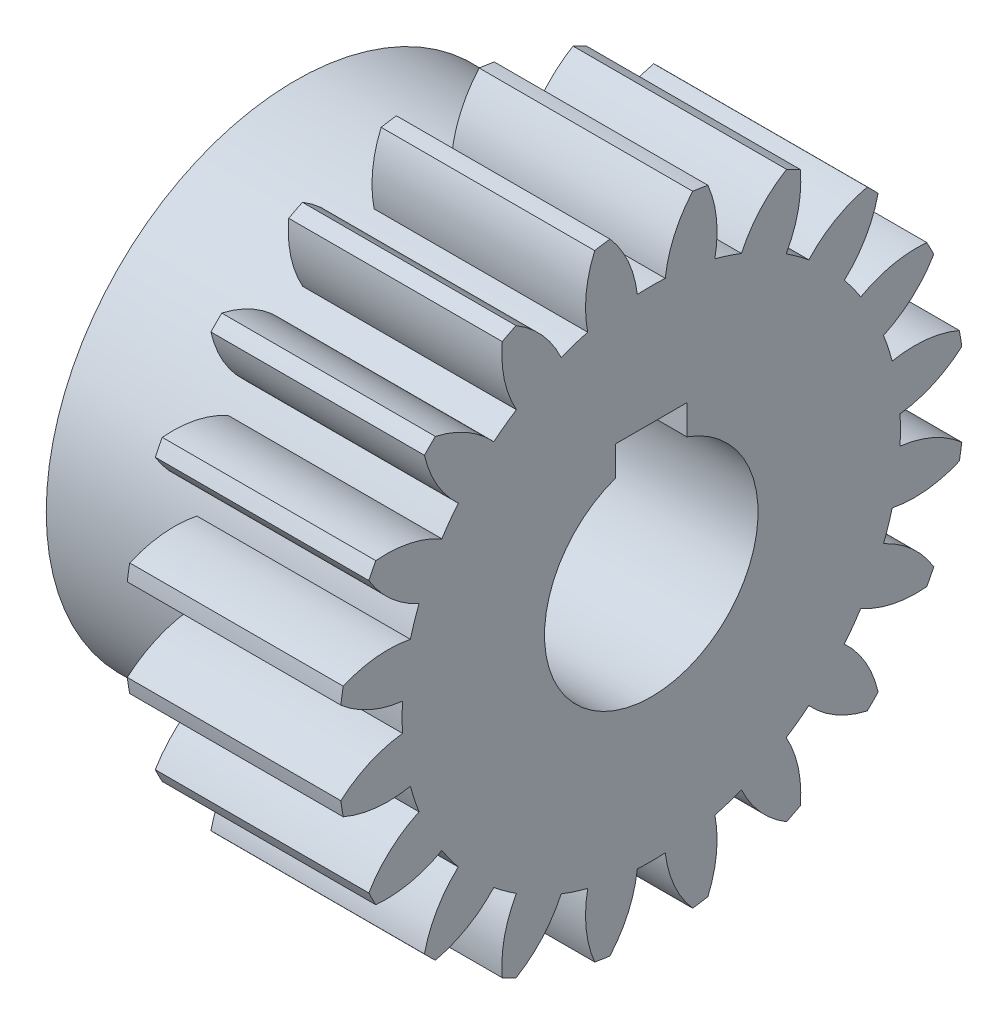
SolidWorks part; units mm, degrees
ref_plane "Plane1" through (0, 0, 0) normal (0, 0, 1) x (1, 0, 0)
ref_plane "Plane2" through (0, 0, 0) normal (0, 1, 0) x (1, 0, 0)
ref_plane "Plane3" through (0, 0, 0) normal (1, 0, 0) x (0, 0, -1)
other "Configuration Table"
sketch "HoldingSke" plane through (0, 0, 0) normal (0, 1, 0) x (1, 0, 0)
  line L0 (0, 0) -> (0.2349, -0.0855)
  line L1 (-15, 0) -> (100, 0) construction
  line L2 (0, 0) -> (-2.1039, 2.3779)
  line L3 (0, 0) -> (-11.863, 4.5341)
  line L4 (0, 0) -> (8.1152, 2.9537)
  line L5 (0, 0) -> (-46.8476, -17.4728)
  line L6 (0, 0) -> (-24.8689, -16.7791)
  line L7 (-2.1039, 2.3779) -> (8.6586, 51.2059)
  line L8 (-76.2, 54.61) -> (-72.9, 54.61)
  line L9 (-71.009, 38.7566) -> (-53.1078, 45.2721)
  line L10 (-76.2, 71.12) -> (104.1128, 71.12)
  line L11 (0, 0) -> (-30, 0)
  line L12 (-76.2, 101.6) -> (-76.073, 101.6)
  line L13 (24.9733, 27.94) -> (52.9518, 28.4284)
  line L14 (24.9733, 27.94) -> (24.9743, 27.94)
  line L15 (24.9733, 27.94) -> (100.4006, 29.5858)
  line L16 (-63.627, -4) -> (-12.827, -4)
  circle A0 centre (0, 0) radius 15
  circle A1 centre (0, 0) radius 34.999
  circle A2 centre (0, 0) radius 37.5
  circle A3 centre (0, 0) radius 15
  dimension "Hub_dia" = 75
  dimension "Bore" = 30
  dimension "MBD" = 30
  dimension "Pitch" = 0.25
  dimension "Overall_len" = 50
  dimension "Thickness" = 30
  dimension "OAL" = 50.0001
  dimension "T_dim" = 3.3
  dimension "Ap" = 20
  dimension "H" = 19.05
  dimension "Pitch_radius" = 180.3128
  dimension "Width" = 30
  dimension "Backlash" = 0.127
  dimension "Addendum_fac" = 1
  dimension "Dedendum_fac" = 1.25
  dimension "Clearance_fac" = 0.25
  dimension "Dedendum_add" = 0.001
  dimension "Module" = 4
sketch "BasProSke" plane through (0, 0, 0) normal (0, 1, 0) x (1, 0, 0)
  line L0 (-10, 0) -> (60, 0) construction
  line L1 (0, 0) -> (0, 44)
  line L2 (0, 0) -> (30, 0)
  line L3 (30, 0) -> (30, 44)
  line L4 (30, 44) -> (0, 44)
  dimension "Thickness" = 30
revolve "Base-Revolve" add sketch "BasProSke" angle 360 about L0
sketch "TooCutSke" plane through (0, 0, 0) normal (1, 0, 0) x (0, 0, -1)
  line L1 (0, 0) -> (0, 107) construction
  line L2 (0, 0) -> (-3.3605, 39.8586) construction
  line L3 (0, 0) -> (-12.4815, 78.8048) construction
  line L4 (-3.3605, 39.8586) -> (-6.2407, 39.4024) construction
  arc A0 (1.9617, 34.944) -> (-1.9617, 34.944) centre (0, 0) ccw
  arc A1 (5.8321, 43.6374) -> (-5.8321, 43.6374) centre (0, 0) ccw
  circle A2 centre (0, 0) radius 40 construction
  circle A3 centre (0, 0) radius 37.5877 construction
  arc A4 (-1.9617, 34.944) -> (-5.8321, 43.6374) centre (-17.8525, 33.0775) ccw
  arc A5 (5.8321, 43.6374) -> (1.9617, 34.944) centre (17.8525, 33.0775) ccw
extrude "ToothCut" cut sketch "TooCutSke" along normal through all
fillet "Breaks" [suppressed] radius 0.08
fillet "RootFillets" [suppressed] radius 1.001
pattern_circular "TeethCuts" count 20 every 18 about axis through (-10, 0, 0) along (1, 0, 0) of "ToothCut", "RootFillets", "Breaks"
sketch "HubNeaOneSke" plane through (0, 0, 0) normal (-1, 0, 0) x (0, 0, 1)
  circle A0 centre (0, 0) radius 34.999
extrude "HubNearOne" add sketch "HubNeaOneSke" along normal blind 20.0001
sketch "HubNeaBotSke" plane through (0, 0, 0) normal (-1, 0, 0) x (0, 0, 1)
  circle A0 centre (0, 0) radius 34.999
extrude "HubNearBoth" [suppressed] add sketch "HubNeaBotSke" along normal blind 10
ref_plane "FarPln" through (30, 0, 0) normal (1, 0, 0) x (0, 0, -1)
sketch "HubFarSke" plane through (30, 0, 0) normal (1, 0, 0) x (0, 0, -1)
  circle A0 centre (0, 0) radius 34.999
extrude "HubFar" [suppressed] add sketch "HubFarSke" along normal blind 10
sketch "BorSke" plane through (0, 0, 0) normal (1, 0, 0) x (0, 0, -1)
  circle A0 centre (0, 0) radius 15
  dimension "Diameter" = 30
extrude "Bore" cut sketch "BorSke" along normal mid plane 100.0001
sketch "KeySke" plane through (0, 0, 0) normal (1, 0, 0) x (0, 0, -1)
  line L0 (-5, 0) -> (-5, 18.3)
  line L1 (-5, 18.3) -> (5, 18.3)
  line L2 (5, 18.3) -> (5, 0)
  line L3 (0, 0) -> (0, 34) construction
  line L4 (-5, 0) -> (5, 0)
  dimension "Offset" = 18.3
  dimension "Width" = 10
extrude "Keyway" cut sketch "KeySke" along normal mid plane 100.0001
pattern_circular "Keyway2" [suppressed] count 2 every 90 about axis through (-10, 0, 0) along (1, 0, 0)
equation "' \"Module@HoldingSke\" = 6.35"
equation "' \"Num_teeth@HoldingSke\" = 12"
equation "' \"Ap@HoldingSke\" =  20"
equation "' \"Ap@HoldingSke\" = 20"
equation "' \"Width@HoldingSke\" = 0.5 * 25.4"
equation "' \"Hub_dia@HoldingSke\"= 1 * 25.4"
equation "' \"Hub_dia@HoldingSke\" = 1 * 25.4"
equation "' \"Overall_len@HoldingSke\" = 1.0 * 25.4"
equation "' \"Bore@HoldingSke\" = 0.75 * 25.4"
equation "' \"T_dim@HoldingSke\" = 0.1 * 25.4"
equation "' \"Width@KeySke\" = 0.25 * 25.4"
equation "' \"Show_teeth@HoldingSke\" = 13"
equation "' \"Backlash@HoldingSke\" = 0.009 * 25.4"
equation "' \"Addendum_fac@HoldingSke\" = 1.0"
equation "' \"Dedendum_fac@HoldingSke\" = 1.25"
equation "' \"Dedendum_add@HoldingSke\" = 0.00005 * 25.4"
equation "' \"Clearance_fac@HoldingSke\" = 0.25"
equation "\"Pitch@HoldingSke\" = 1 / \"Module@HoldingSke\""
equation "\"Overcut_dia@TooCutSke\" = (\"Num_teeth@HoldingSke\" + 2 * \"Addendum_fac@HoldingSke\") / \"Pitch@HoldingSke\" + 0.002 * 25.4"
equation "\"Pitch_dia@TooCutSke\" = \"Num_teeth@HoldingSke\" / \"Pitch@HoldingSke\""
equation "\"Base_dia@TooCutSke\" = \"Num_teeth@HoldingSke\" / \"Pitch@HoldingSke\" * cos((\"Ap@HoldingSke\"  * 3.14159265 / 180))"
equation "\"Root_dia@TooCutSke\" = (\"Num_teeth@HoldingSke\" + 2) / \"Pitch@HoldingSke\" - 2 * (\"Addendum_fac@HoldingSke\" + \"Dedendum_fac@HoldingSke\") / \"Pitch@HoldingSke\" - \"Dedendum_add@HoldingSke\" * 2"
equation "\"Half_ang@TooCutSke\" = 180 / \"Num_teeth@HoldingSke\""
equation "\"Half_CT@TooCutSke\" = \"Num_teeth@HoldingSke\" / \"Pitch@HoldingSke\" * sin((3.14159265 / 2 / \"Num_teeth@HoldingSke\")) / 2 - 7 * \"Backlash@HoldingSke\" / 4"
equation "\"Flank_rad@TooCutSke\" = \"Num_teeth@HoldingSke\" / \"Pitch@HoldingSke\" / 5"
equation "\"Radius@RootFillets\" = \"Clearance_fac@HoldingSke\" / \"Pitch@HoldingSke\" + \"Dedendum_add@HoldingSke\""
equation "\"Break_rad@Breaks\" = 0.02 / \"Pitch@HoldingSke\""
equation "\"Thickness@HoldingSke\" = \"Width@HoldingSke\""
equation "\"OAL@HoldingSke\" = \"Thickness@HoldingSke\""
equation "\"MHD@HoldingSke\" = (\"Num_teeth@HoldingSke\" + 2) / \"Pitch@HoldingSke\" - 2 * (\"Addendum_fac@HoldingSke\" + \"Dedendum_fac@HoldingSke\")  / \"Pitch@HoldingSke\" - \"Dedendum_add@HoldingSke\" * 2"
equation "\"MBD@HoldingSke\" = (\"Num_teeth@HoldingSke\" + 2) / \"Pitch@HoldingSke\" - 2 * (\"Addendum_fac@HoldingSke\" + \"Dedendum_fac@HoldingSke\")  / \"Pitch@HoldingSke\" - \"Dedendum_add@HoldingSke\" * 2 - 0.002 * 25.4"
equation "\"MHD@HoldingSke\" = ((sgn( \"MHD@HoldingSke\" - \"Hub_dia@HoldingSke\" )-1)*( \"MHD@HoldingSke\" - \"Hub_dia@HoldingSke\" ))/-2+ \"Hub_dia@HoldingSke\""
equation "\"MBD@HoldingSke\" = ((sgn( \"MBD@HoldingSke\" - \"Bore@HoldingSke\" )-1)*( \"MBD@HoldingSke\" - \"Bore@HoldingSke\" ))/-2+ \"Bore@HoldingSke\""
equation "\"OAL@HoldingSke\" = ((sgn( \"OAL@HoldingSke\" - \"Overall_len@HoldingSke\" )+1)*( \"OAL@HoldingSke\" - \"Overall_len@HoldingSke\" ))/2 + \"Overall_len@HoldingSke\" + 0.000002 * 25.4"
equation "\"Num_teeth@TeethCuts\" = int( \"Show_teeth@HoldingSke\" ) + 1"
equation "\"Num_teeth@TeethCuts\" = ((sgn( \"Num_teeth@TeethCuts\" - \"Num_teeth@HoldingSke\" )-1)*( \"Num_teeth@TeethCuts\" - \"Num_teeth@HoldingSke\" ))/-2+ \"Num_teeth@HoldingSke\""
equation "\"Num_teeth@TeethCuts\" = ((sgn( \"Num_teeth@TeethCuts\" - 2.0)+1)*( \"Num_teeth@TeethCuts\" - 2.0))/2 +2.0"
equation "\"Angle@TeethCuts\" = 360.0 / \"Num_teeth@HoldingSke\""
equation "\"Diameter@BasProSke\" = (\"Num_teeth@HoldingSke\" + 2 * \"Addendum_fac@HoldingSke\") / \"Pitch@HoldingSke\""
equation "\"Thickness@BasProSke\"  = \"Thickness@HoldingSke\""
equation "' \"Fillet_rad@BasProSke\" =  \"Thickness@HoldingSke\" * 0.05"
equation "' \"Fillet_rad@BasProSke\" = \"Thickness@HoldingSke\" * 0.05"
equation "\"MHD@HoldingSke\" = ((sgn( \"MHD@HoldingSke\" - \"Root_dia@TooCutSke\" )-1)*( \"MHD@HoldingSke\" - \"Root_dia@TooCutSke\" ))/-2+ \"Root_dia@TooCutSke\""
equation "\"Diameter@HubNeaOneSke\" = \"MHD@HoldingSke\""
equation "\"Length@HubNearOne\" = \"OAL@HoldingSke\" - \"Thickness@BasProSke\""
equation "\"Diameter@HubNeaBotSke\" = \"MHD@HoldingSke\""
equation "\"Length@HubNearBoth\" = ( \"OAL@HoldingSke\" - \"Thickness@BasProSke\" ) / 2.0"
equation "\"Thickness@FarPln\" = \"Thickness@BasProSke\""
equation "\"Diameter@HubFarSke\" = \"MHD@HoldingSke\""
equation "\"Length@HubFar\" = ( \"OAL@HoldingSke\" - \"Thickness@BasProSke\" ) / 2.0"
equation "\"Diameter@BorSke\" = \"MBD@HoldingSke\""
equation "\"D1@Bore\" = \"OAL@HoldingSke\" * 2.0"
equation "\"D1@Keyway\" = \"OAL@HoldingSke\" * 2.0"
equation "\"Offset@KeySke\" = \"T_dim@HoldingSke\" + \"MBD@HoldingSke\" / 2.0"
